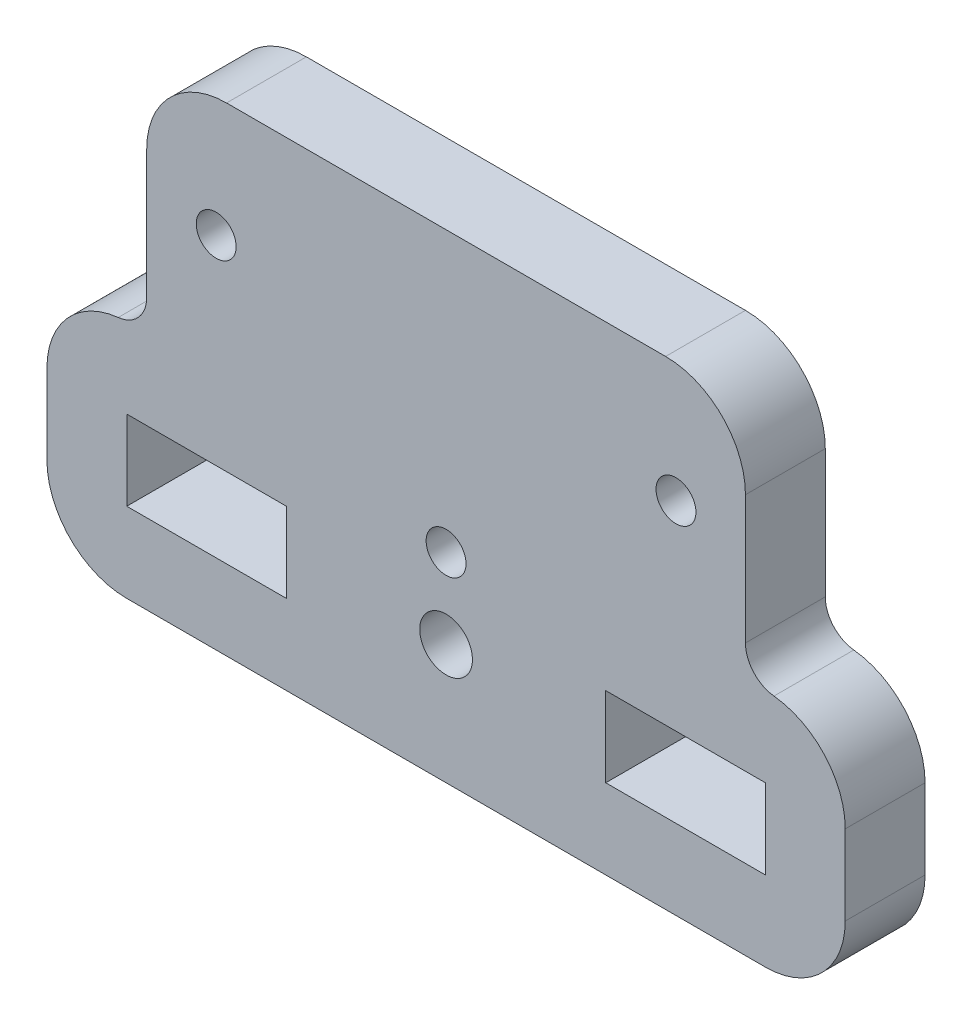
SolidWorks part; units mm, degrees
ref_plane "Front Plane" through (0, 0, 0) normal (0, 0, 1) x (1, 0, 0)
ref_plane "Top Plane" through (0, 0, 0) normal (0, 1, 0) x (1, 0, 0)
ref_plane "Right Plane" through (0, 0, 0) normal (1, 0, 0) x (0, 0, -1)
sketch "Sketch1" plane through (0, 0, 0) normal (0, 0, 1) x (1, 0, 0)
  line L1 (-31.75, -9.525) -> (31.75, -9.525)
  line L2 (-31.75, -9.525) -> (-31.75, 9.525)
  line L3 (-31.75, 9.525) -> (31.75, 9.525)
  line L4 (31.75, -9.525) -> (31.75, 9.525)
  line L5 (-31.75, -9.525) -> (31.75, 9.525) construction
  line L6 (-31.75, 9.525) -> (31.75, -9.525) construction
  point P0 (0, 0)
  dimension "D1" = 63.5
  dimension "D2" = 19.05
extrude "Boss-Extrude1" add sketch "Sketch1" along normal blind 6.35
sketch "Sketch2" plane through (0, 0, 6.35) normal (0, 0, 1) x (1, 0, 0)
  line L0 (0, 0) -> (0, 19.7518) construction
  circle A0 centre (0, 0) radius 2.0955
  dimension "D1" = 4.191
extrude "Cut-Extrude1" cut sketch "Sketch2" against normal through all
sketch "Sketch3" plane through (0, 0, 6.35) normal (0, 0, 1) x (1, 0, 0)
  line L0 (0, 0) -> (-39.1173, 0) construction
  line L1 (-25.4, -3.175) -> (-12.7, -3.175)
  line L2 (-25.4, -3.175) -> (-25.4, 3.175)
  line L3 (-25.4, 3.175) -> (-12.7, 3.175)
  line L4 (-12.7, -3.175) -> (-12.7, 3.175)
  line L5 (-25.4, -3.175) -> (-12.7, 3.175) construction
  line L6 (-25.4, 3.175) -> (-12.7, -3.175) construction
  point P0 (-19.05, 0)
  dimension "D1" = 12.7
  dimension "D2" = 6.35
  dimension "D3" = 12.7
extrude "Cut-Extrude2" cut sketch "Sketch3" against normal through all
mirror "Mirror1" about plane through (0, 0, 0) normal (1, 0, 0) of "Cut-Extrude2"
sketch "Sketch4" plane through (0, 0, 6.35) normal (0, 0, 1) x (1, 0, 0)
  line L0 (31.75, 9.525) -> (-31.75, 9.525) construction
  line L1 (-23.8125, 28.575) -> (23.8125, 28.575)
  line L2 (-23.8125, 28.575) -> (-23.8125, 9.525)
  line L3 (-23.8125, 9.525) -> (23.8125, 9.525)
  line L4 (23.8125, 28.575) -> (23.8125, 9.525)
  line L5 (-23.8125, 28.575) -> (23.8125, 9.525) construction
  line L6 (-23.8125, 9.525) -> (23.8125, 28.575) construction
  line L7 (0, 0) -> (0, 29.4973) construction
  line L8 (-12.7, 3.175) -> (-25.4, 3.175) construction
  point P0 (0, 19.05)
  dimension "D1" = 47.625
  dimension "D2" = 25.4
extrude "Boss-Extrude2" add sketch "Sketch4" against normal up to surface (6.35 mm away) up to face at (-19.05, 0, 0)
sketch "Sketch5" plane through (0, 0, 6.35) normal (0, 0, 1) x (1, 0, 0)
  line L0 (0, 0) -> (0, 27.4661) construction
  line L1 (32.0224, 19.05) -> (-3.0527, 19.05) construction
  line L2 (23.8125, 28.575) -> (-23.8125, 28.575) construction
  line L3 (31.75, 9.525) -> (23.8125, 9.525) construction
  circle A0 centre (-18.288, 19.05) radius 1.5875
  dimension "D1" = 3.175
  dimension "D2" = 36.576
extrude "Cut-Extrude3" cut sketch "Sketch5" against normal through all
mirror "Mirror2" about plane through (0, 0, 0) normal (1, 0, 0) of "Cut-Extrude3"
sketch "Sketch6" plane through (0, 0, 6.35) normal (0, 0, 1) x (1, 0, 0)
  line L0 (-18.288, 19.05) -> (18.288, 19.05) construction
  line L1 (0, 0) -> (0, 6.35) construction
  circle A0 centre (0, 6.35) radius 1.5875
  dimension "D2" = 3.175
  dimension "D1" = 12.7
extrude "Cut-Extrude4" cut sketch "Sketch6" against normal through all
fillet "Fillet3" radius 6.35 6 edges at (23.8125, 28.575, 3.175) (-23.8125, 28.575, 3.175) (31.75, -9.525, 3.175) (-31.75, -9.525, 3.175) (-31.75, 9.525, 3.175) (31.75, 9.525, 3.175)
fillet "Fillet4" radius 2.54 2 edges
